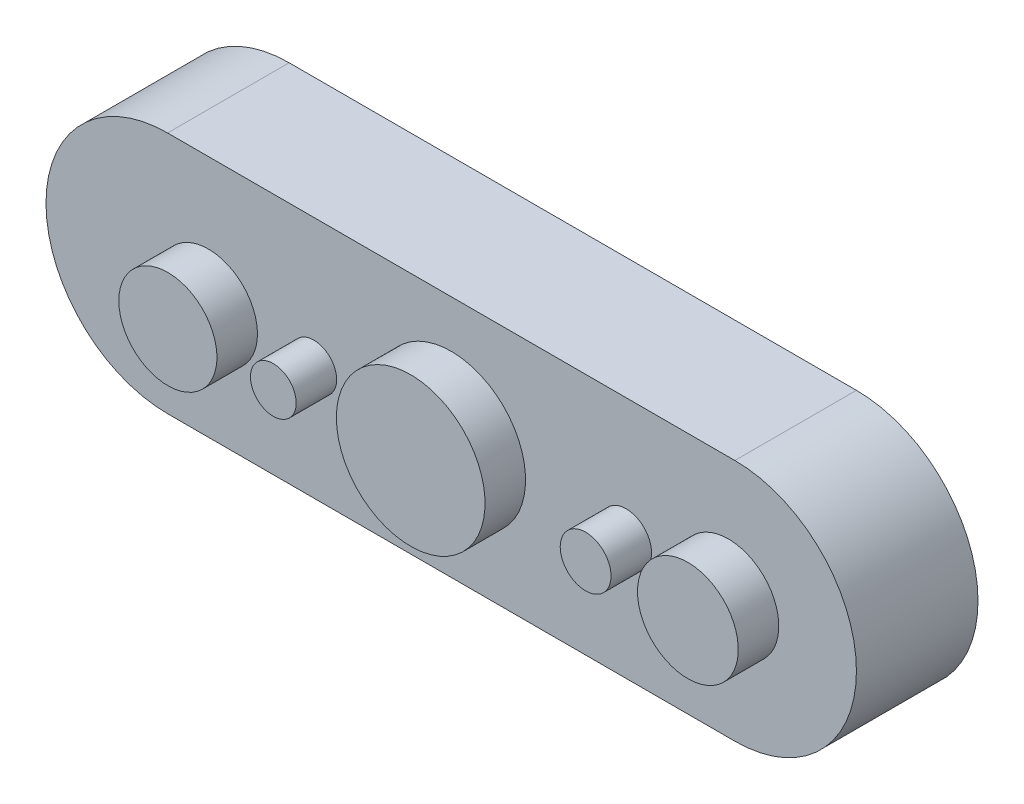
SolidWorks part; units mm, degrees
ref_plane "Front Plane" through (0, 0, 0) normal (0, 0, 1) x (1, 0, 0)
ref_plane "Top Plane" through (0, 0, 0) normal (0, 1, 0) x (1, 0, 0)
ref_plane "Right Plane" through (0, 0, 0) normal (1, 0, 0) x (0, 0, -1)
ref_plane "Plane1" through (0, 0, 0) normal (0, 0, -1) x (-1, 0, 0)
sketch "Sketch1" plane through (0, 0, 0) normal (0, 0, -1) x (-1, 0, 0)
  line L0 (3.5, 1.5) -> (-3.5, 1.5)
  line L1 (-3.5, -1.5) -> (3.5, -1.5)
  arc A0 (3.5, -1.5) -> (3.5, 1.5) centre (3.5, 0) ccw
  arc A1 (-3.5, 1.5) -> (-3.5, -1.5) centre (-3.5, 0) ccw
extrude "Boss-Extrude1" add sketch "Sketch1" against normal blind 1.5
ref_plane "Plane2" through (0, 0, 0) normal (0, -1, 0) x (1, 0, 0)
sketch "Sketch2" plane through (0, 0, 0) normal (0, -1, 0) x (1, 0, 0)
  line L0 (4.042, 2) -> (3.4201, 2)
  line L1 (3.4201, 2) -> (3.4201, 1.5)
  line L2 (3.4201, 1.5) -> (4.042, 1.5)
  line L3 (4.042, 1.5) -> (4.042, 2)
  line L4 (3.4201, 2) -> (3.4201, 1.5) construction
revolve "Revolve1" add sketch "Sketch2" angle 360 about L4
sketch "Sketch3" plane through (0, 0, 0) normal (0, -1, 0) x (1, 0, 0)
  line L0 (2.4721, 2) -> (2.1585, 2)
  line L1 (2.1585, 2) -> (2.1585, 1.5)
  line L2 (2.1585, 1.5) -> (2.4721, 1.5)
  line L3 (2.4721, 1.5) -> (2.4721, 2)
  line L4 (2.1585, 2) -> (2.1585, 1.5) construction
revolve "Revolve2" add sketch "Sketch3" angle 360 about L4
sketch "Sketch4" plane through (0, 0, 0) normal (0, -1, 0) x (1, 0, 0)
  line L0 (0.9173, 2) -> (0, 2)
  line L1 (0, 2) -> (0, 1.5)
  line L2 (0, 1.5) -> (0.9173, 1.5)
  line L3 (0.9173, 1.5) -> (0.9173, 2)
  line L4 (0, 2) -> (0, 1.5) construction
revolve "Revolve3" add sketch "Sketch4" angle 360 about L4
ref_plane "Plane3" through (0, -0.0936, 0) normal (0, -1, 0) x (1, 0, 0)
sketch "Sketch5" plane through (0, -0.0936, 0) normal (0, -1, 0) x (1, 0, 0)
  line L0 (-1.413, 2) -> (-1.6953, 2)
  line L1 (-1.6953, 2) -> (-1.6953, 1.5)
  line L2 (-1.6953, 1.5) -> (-1.413, 1.5)
  line L3 (-1.413, 1.5) -> (-1.413, 2)
  line L4 (-1.6953, 2) -> (-1.6953, 1.5) construction
revolve "Revolve4" add sketch "Sketch5" angle 360 about L4
sketch "Sketch6" plane through (0, -0.0936, 0) normal (0, -1, 0) x (1, 0, 0)
  line L0 (-2.3911, 2) -> (-2.9963, 2)
  line L1 (-2.9963, 2) -> (-2.9963, 1.5)
  line L2 (-2.9963, 1.5) -> (-2.3911, 1.5)
  line L3 (-2.3911, 1.5) -> (-2.3911, 2)
  line L4 (-2.9963, 2) -> (-2.9963, 1.5) construction
revolve "Revolve5" add sketch "Sketch6" angle 360 about L4
